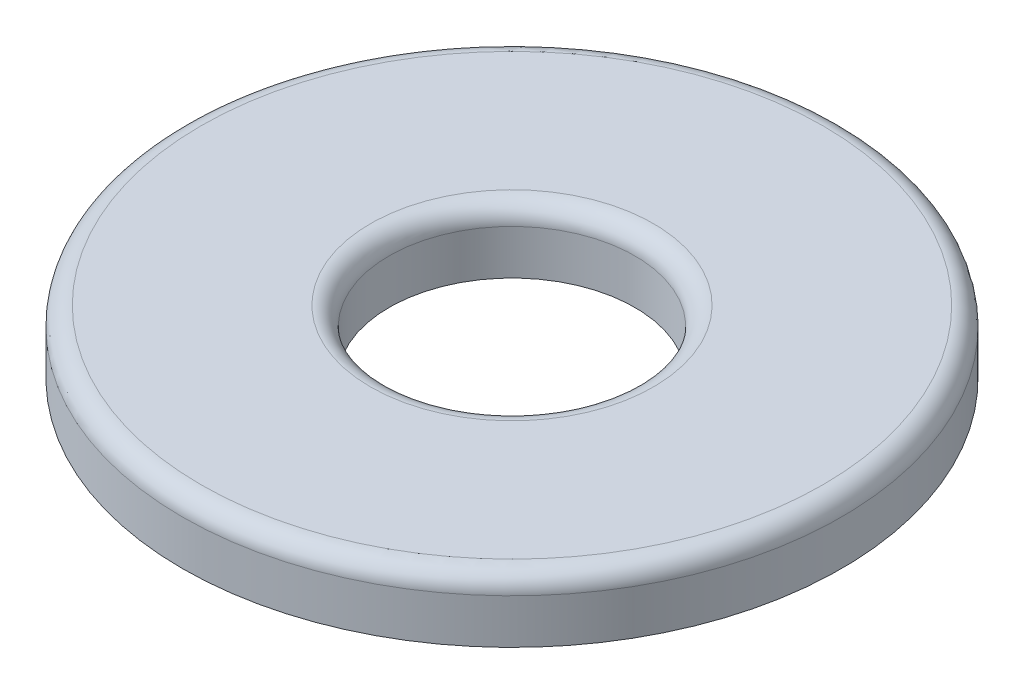
SolidWorks part; units mm, degrees
ref_plane "Front" through (0, 0, 0) normal (0, 0, 1) x (1, 0, 0)
ref_plane "Top" through (0, 0, 0) normal (0, 1, 0) x (1, 0, 0)
ref_plane "Right" through (0, 0, 0) normal (1, 0, 0) x (0, 0, -1)
sketch "Sketch1" plane through (0, 0, 0) normal (1, 0, 0) x (0, 0, -1)
  line L0 (0, 2.1845) -> (0, 0) construction
  line L1 (0, 0) -> (3.7485, 0) construction
  line L2 (1.65, 0) -> (4.425, 0)
  line L3 (4.425, 0) -> (4.425, 0.6)
  line L4 (4.175, 0.85) -> (1.9, 0.85)
  line L5 (1.65, 0.6) -> (1.65, 0)
  line L6 (3.0375, 0) -> (3.0375, 0.85) construction
  arc A0 (4.425, 0.6) -> (4.175, 0.85) centre (4.175, 0.6) ccw
  arc A1 (1.9, 0.85) -> (1.65, 0.6) centre (1.9, 0.6) ccw
  dimension "D4" = 0.25
  dimension "D1" = 3.3
  dimension "D2" = 8.85
  dimension "D3" = 0.85
revolve "Revolve1" add sketch "Sketch1" angle 360 about L0
